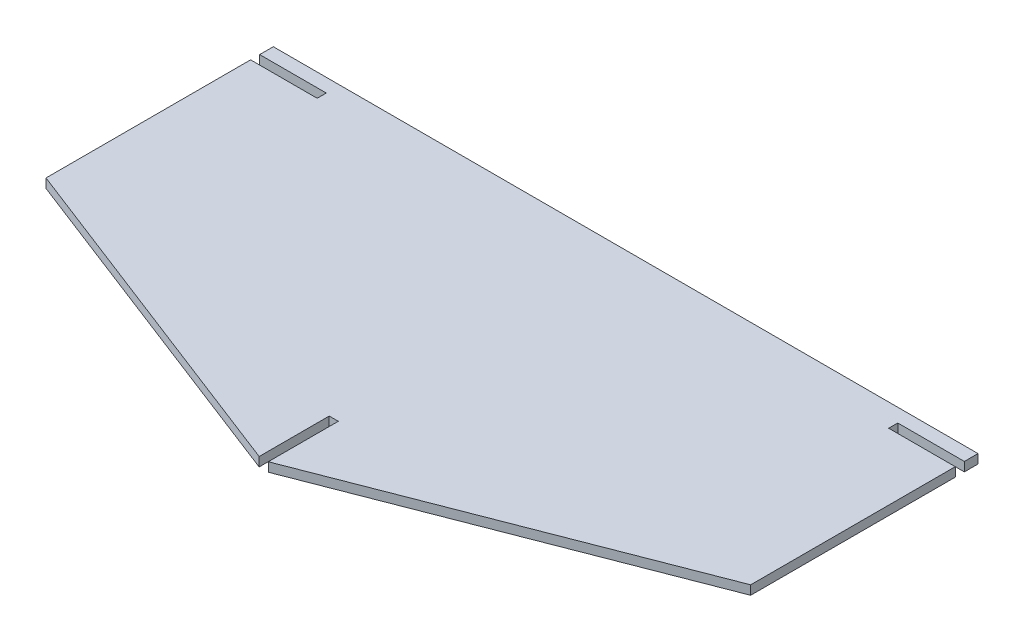
SolidWorks part; units mm, degrees
ref_plane "Front Plane" through (0, 0, 0) normal (0, 0, 1) x (1, 0, 0)
ref_plane "Top Plane" through (0, 0, 0) normal (0, 1, 0) x (1, 0, 0)
ref_plane "Right Plane" through (0, 0, 0) normal (1, 0, 0) x (0, 0, -1)
sketch "Sketch1" plane through (0, 0, 0) normal (0, 1, 0) x (1, 0, 0)
  line L0 (0, -100) -> (155, -160)
  line L1 (0, 0) -> (310, 0)
  line L2 (0, 0) -> (0, -100)
  line L3 (0, -100) -> (310, -100)
  line L4 (310, 0) -> (310, -100)
  line L5 (155, -160) -> (310, -100)
  line L6 (155, -160) -> (155, -100) construction
  line L8 (0, -6) -> (29.3, -6)
  line L9 (0, -6) -> (0, -10)
  line L10 (0, -10) -> (29.3, -10)
  line L11 (29.3, -6) -> (29.3, -10)
  line L12 (310, -6) -> (280.7, -6)
  line L13 (310, -6) -> (310, -10)
  line L14 (310, -10) -> (280.7, -10)
  line L15 (280.7, -6) -> (280.7, -10)
  line L16 (153, -160) -> (157, -160)
  line L17 (153, -160) -> (153, -128.4)
  line L18 (153, -128.4) -> (157, -128.4)
  line L19 (157, -160) -> (157, -128.4)
  point P19 (155, -160)
  dimension "D1" = 310
  dimension "D2" = 100
  dimension "D3" = 60
  dimension "D4" = 4
  dimension "D5" = 6
  dimension "D6" = 29.3
  dimension "D7" = 31.6
extrude "Boss-Extrude1" add sketch "Sketch1" along normal blind 4 contours L0 L6 L3 | L4 L1 L2 L3 | L6 L5 L3
ref_plane "Plane1" through (155, 0, 0) normal (-1, 0, 0) x (0, 0, 1)
